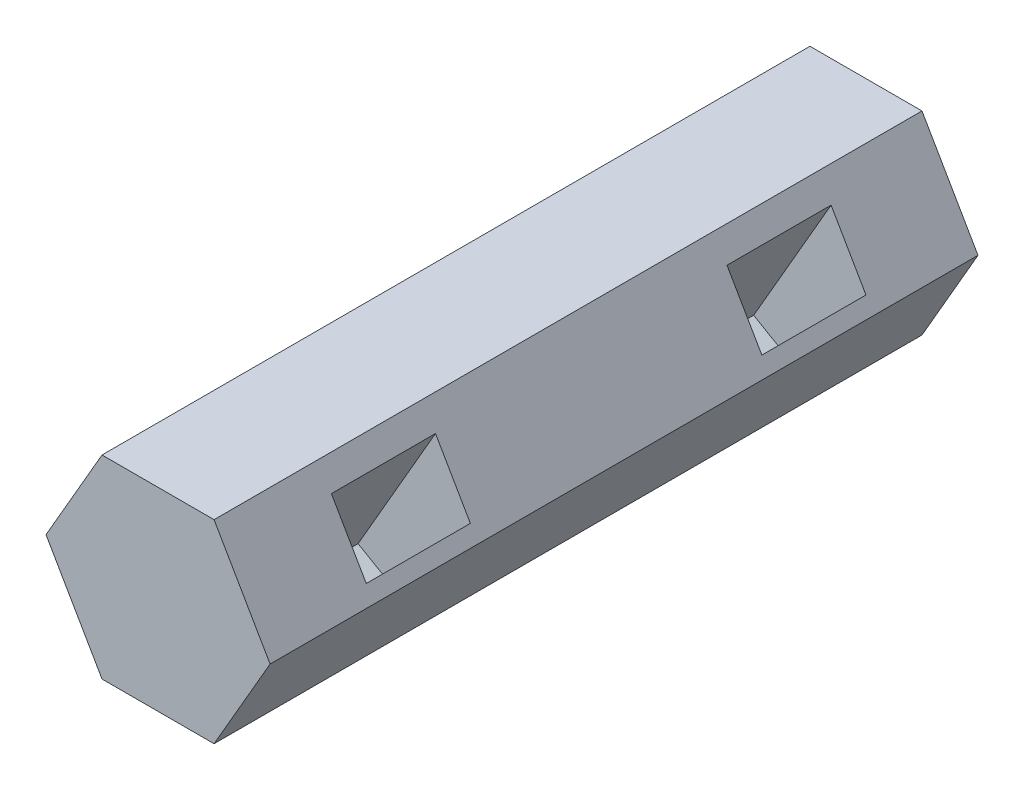
SolidWorks part; units mm, degrees
ref_plane "Plan de face" through (0, 0, 0) normal (0, 0, 1) x (1, 0, 0)
ref_plane "Plan de dessus" through (0, 0, 0) normal (0, 1, 0) x (1, 0, 0)
ref_plane "Plan de droite" through (0, 0, 0) normal (1, 0, 0) x (0, 0, -1)
sketch "Esquisse1" plane through (0, 0, 0) normal (0, 0, 1) x (1, 0, 0)
  line L1 (5, 8.6603) -> (-5, 8.6603) construction
  line L2 (-5, 8.6603) -> (-10, 0) construction
  line L3 (-10, 0) -> (-5, -8.6603) construction
  line L4 (-5, -8.6603) -> (5, -8.6603) construction
  line L5 (5, -8.6603) -> (10, 0) construction
  line L6 (10, 0) -> (5, 8.6603) construction
  line L7 (-2.6906, 4.6603) -> (-5.3812, 0)
  line L8 (-5.3812, 0) -> (-2.6906, -4.6603)
  line L9 (-2.6906, -4.6603) -> (2.6906, -4.6603)
  line L10 (2.6906, -4.6603) -> (5.3812, 0)
  line L11 (5.3812, 0) -> (2.6906, 4.6603)
  line L12 (2.6906, 4.6603) -> (-2.6906, 4.6603)
  circle A0 centre (0, 0) radius 8.6603 construction
  circle A1 centre (0, 0) radius 4.6603 construction
  dimension "D1" = 10
  dimension "D2" = 4
extrude "Boss.-Extru.1" add sketch "Esquisse1" along normal blind 34
ref_plane "Plan1" through (0, 0, 5) normal (0, 0, -1) x (-1, 0, 0)
sketch "Esquisse2" plane through (0, 0, 5) normal (0, 0, 1) x (1, 0, 0)
  line L0 (3.6573, 4.1347) -> (-0.3927, -2.8801)
  line L3 (-0.3927, -2.8801) -> (2.1188, -4.3301)
  line L4 (2.1188, -4.3301) -> (6.1688, 2.6847)
  line L6 (6.1688, 2.6847) -> (3.6573, 4.1347)
  line L7 (2.6906, -4.6603) -> (5.3812, 0) construction
  point P2 (3.6752, 4.1188)
  point P3 (5.8026, 2.1094)
  point P4 (0, 0)
  point P5 (0, 0)
  point P6 (0, 0)
  point P7 (0, 0)
  point P9 (0, 0)
  point P11 (6.24, 2.9081)
  point P13 (0, 0)
  dimension "D1" = 1.1
  dimension "D3" = 2.9
extrude "Enlèv. mat.-Extru.1" cut sketch "Esquisse2" along normal blind 5
ref_plane "Plan2" through (0, 0, 17) normal (0, 0, -1) x (-1, 0, 0)
mirror "Symétrie1" about plane through (0, 0, 17) normal (0, 0, -1) of "Enlèv. mat.-Extru.1"
